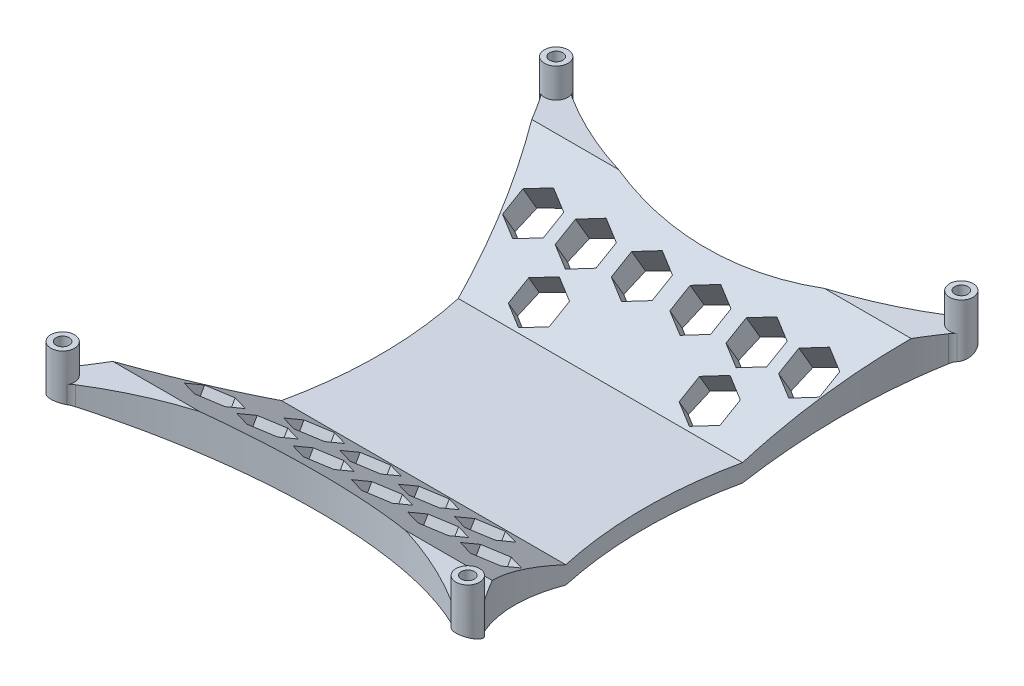
SolidWorks part; units mm, degrees
ref_plane "Front Plane" through (0, 0, 0) normal (0, 0, 1) x (1, 0, 0)
ref_plane "Top Plane" through (0, 0, 0) normal (0, 1, 0) x (1, 0, 0)
ref_plane "Right Plane" through (0, 0, 0) normal (1, 0, 0) x (0, 0, -1)
sketch "Sketch2" plane through (0, 0, 0) normal (0, 1, 0) x (1, 0, 0)
  line L0 (0, 2.54) -> (87.3125, 2.54) construction
  line L1 (89.8525, 0) -> (89.8525, -106.3625) construction
  line L2 (87.3125, -108.9025) -> (0, -108.9025) construction
  line L3 (-2.54, -106.3625) -> (-2.54, 0) construction
  line L4 (4.3994, -106.3625) -> (82.9131, -106.3625)
  line L5 (0, -101.9631) -> (0, -4.3994)
  line L6 (4.3994, 0) -> (82.9131, 0)
  line L7 (87.3125, -4.3994) -> (87.3125, -101.9631)
  circle A0 centre (0, 0) radius 1.4224
  circle A1 centre (87.3125, 0) radius 1.4224
  circle A2 centre (0, -106.3625) radius 1.4224
  circle A3 centre (87.3125, -106.3625) radius 1.4224
  arc A4 (-2.54, 0) -> (0, 2.54) centre (0, 0) cw
  arc A5 (89.8525, 0) -> (87.3125, 2.54) centre (87.3125, 0) ccw
  arc A6 (87.3125, -108.9025) -> (89.8525, -106.3625) centre (87.3125, -106.3625) ccw
  arc A7 (0, -108.9025) -> (-2.54, -106.3625) centre (0, -106.3625) cw
  arc A8 (-2.54, -106.3625) -> (-1.27, -104.1628) centre (0, -106.3625) cw
  arc A9 (0, -108.9025) -> (2.1997, -107.6325) centre (0, -106.3625) ccw
  arc A10 (-2.54, 0) -> (-1.27, -2.1997) centre (0, 0) ccw
  arc A11 (0, 2.54) -> (2.1997, 1.27) centre (0, 0) cw
  arc A12 (87.3125, 2.54) -> (85.1128, 1.27) centre (87.3125, 0) ccw
  arc A13 (88.5825, -2.1997) -> (89.8525, 0) centre (87.3125, 0) ccw
  arc A14 (85.1128, 1.27) -> (82.9131, 0) centre (82.9131, 2.54) cw
  arc A15 (87.3125, -4.3994) -> (88.5825, -2.1997) centre (89.8525, -4.3994) cw
  arc A16 (2.1997, 1.27) -> (4.3994, 0) centre (4.3994, 2.54) ccw
  arc A17 (0, -4.3994) -> (-1.27, -2.1997) centre (-2.54, -4.3994) ccw
  arc A18 (-1.27, -104.1628) -> (0, -101.9631) centre (-2.54, -101.9631) ccw
  arc A19 (2.1997, -107.6325) -> (4.3994, -106.3625) centre (4.3994, -108.9025) cw
  arc A20 (85.1128, -107.6325) -> (87.3125, -108.9025) centre (87.3125, -106.3625) ccw
  arc A21 (88.5825, -104.1628) -> (89.8525, -106.3625) centre (87.3125, -106.3625) cw
  arc A22 (82.9131, -106.3625) -> (85.1128, -107.6325) centre (82.9131, -108.9025) cw
  arc A23 (87.3125, -101.9631) -> (88.5825, -104.1628) centre (89.8525, -101.9631) ccw
  point P37 (84.7725, 0)
  point P40 (87.3125, -2.54)
  point P43 (2.54, 0)
  point P46 (0, -2.54)
  point P49 (0, -103.8225)
  point P52 (2.54, -106.3625)
  point P57 (84.7725, -106.3625)
  point P60 (87.3125, -103.8225)
  dimension "D1" = 2.8448
  dimension "D2" = 87.3125
  dimension "D8" = 2.54
  dimension "D9" = 2.54
  dimension "D10" = 2.54
  dimension "D11" = 2.54
  dimension "D20" = 2.54
  dimension "D21" = 2.54
  dimension "D22" = 2.54
  dimension "D23" = 2.54
  dimension "D24" = 2.54
  dimension "D25" = 2.54
  dimension "D26" = 2.54
  dimension "D27" = 2.54
  dimension "D3" = 106.3625
  dimension "D4" = 2.54
  dimension "D5" = 2.54
  dimension "D6" = 2.54
  dimension "D7" = 2.54
  dimension "D12" = 2.54
  dimension "D13" = 2.54
  dimension "D14" = 2.54
  dimension "D15" = 2.54
  dimension "D16" = 2.54
  dimension "D17" = 2.54
  dimension "D18" = 2.54
  dimension "D19" = 2.54
extrude "Boss-Extrude1" add sketch "Sketch2" along normal blind 19.05
sketch "Sketch3" plane through (0, 0, 0) normal (0, -1, 0) x (1, 0, 0)
  line L0 (3.1294, 106.7028) -> (84.1831, 106.7028)
  line L1 (-0.3403, 103.2331) -> (-0.3403, 3.1294)
  line L2 (3.1294, -0.3403) -> (84.1831, -0.3403)
  line L3 (87.6528, 103.2331) -> (87.6528, 3.1294)
  arc A0 (-0.3403, 103.2331) -> (-0.3403, 3.1294) centre (-73.8115, 53.1813) cw
  arc A1 (0, 101.9631) -> (-1.27, 104.1628) centre (-2.54, 101.9631) ccw construction
  arc A2 (-1.27, 2.1997) -> (0, 4.3994) centre (-2.54, 4.3994) ccw construction
  arc A3 (3.1294, 106.7028) -> (84.1831, 106.7028) centre (43.6563, 171.232) ccw
  arc A4 (2.1997, 107.6325) -> (4.3994, 106.3625) centre (4.3994, 108.9025) ccw construction
  arc A5 (82.9131, 106.3625) -> (85.1128, 107.6325) centre (82.9131, 108.9025) ccw construction
  arc A6 (87.6528, 103.2331) -> (87.6528, 3.1294) centre (161.124, 53.1813) ccw
  arc A7 (88.5825, 104.1628) -> (87.3125, 101.9631) centre (89.8525, 101.9631) ccw construction
  arc A8 (87.3125, 4.3994) -> (88.5825, 2.1997) centre (89.8525, 4.3994) ccw construction
  arc A9 (3.1294, -0.3403) -> (84.1831, -0.3403) centre (43.6562, -64.8695) cw
  arc A10 (4.3994, 0) -> (2.1997, -1.27) centre (4.3994, -2.54) ccw construction
  arc A11 (85.1128, -1.27) -> (82.9131, 0) centre (82.9131, -2.54) ccw construction
  dimension "D1" = 88.9
  dimension "D2" = 76.2
  dimension "D3" = 88.9
  dimension "D4" = 76.2
extrude "Cut-Extrude1" cut sketch "Sketch3" against normal through all
sketch "Sketch4" plane through (0, 0, 0) normal (1, 0, 0) x (0, 0, -1)
  line L0 (2.54, 15.875) -> (-34.1313, 0) construction
  line L1 (-34.1313, 0) -> (-72.2313, 0) construction
  line L2 (-72.2313, 0) -> (-108.9025, 15.875) construction
  line L4 (-108.9025, 15.875) -> (-108.9025, 0)
  line L5 (-3.1294, 0) -> (-103.2331, 0) construction
  line L6 (-3.1294, 19.05) -> (-3.1294, 0) construction
  line L7 (-103.2331, 19.05) -> (-103.2331, 0) construction
  line L8 (-108.9025, 0) -> (-72.2313, 0)
  line L9 (-72.2313, 0) -> (-108.9025, 15.875)
  line L10 (-3.1294, 0) -> (-3.1294, 19.05) construction
  line L11 (-3.1294, 19.05) -> (-103.2331, 19.05) construction
  line L12 (-103.2331, 19.05) -> (-103.2331, 0) construction
  line L15 (2.54, 0) -> (2.54, 19.05) construction
  line L16 (-3.1294, 19.05) -> (-103.2331, 19.05) construction
  line L17 (-108.9025, 19.05) -> (-108.9025, 0) construction
  line L18 (-8.0285, 19.05) -> (-34.1313, 3.81) construction
  line L19 (-34.1313, 3.81) -> (-72.2313, 3.81) construction
  line L20 (-72.2313, 3.81) -> (-98.334, 19.05) construction
  line L21 (-98.334, 19.05) -> (-103.2331, 19.05) construction
  line L22 (-8.0285, 19.05) -> (-3.1294, 19.05) construction
  line L23 (2.54, 15.875) -> (2.54, 19.05) construction
  line L24 (2.54, 19.05) -> (-3.1294, 19.05) construction
  line L25 (-103.2331, 19.05) -> (-108.9025, 19.05) construction
  line L26 (-108.9025, 19.05) -> (-108.9025, 15.875) construction
  line L27 (-98.334, 19.05) -> (-72.2313, 3.81)
  line L28 (-72.2313, 3.81) -> (-34.1313, 3.81)
  line L29 (-34.1313, 3.81) -> (-8.0285, 19.05)
  line L30 (-8.0285, 19.05) -> (-98.334, 19.05)
  line L31 (-34.1313, 0) -> (2.54, 15.875)
  line L32 (2.54, 15.875) -> (2.54, 0)
  line L33 (2.54, 0) -> (2.54, 19.05) construction
  line L34 (2.54, 0) -> (-34.1313, 0)
  point P2 (-53.1813, 0)
  point P5 (-53.1813, 19.05)
  point P16 (-53.1813, 3.81)
  point P17 (-53.1813, 0)
  dimension "D1" = 3.175
  dimension "D2" = 38.1
  dimension "D3" = 38.1
  dimension "D4" = 3.81
  dimension "D5" = 30.226
extrude "Cut-Extrude3" cut sketch "Sketch4" along normal through all and the other way through all
ref_plane "Plane1" through (0, 19.05, 0) normal (0, 1, 0) x (1, 0, 0)
sketch "Sketch5" plane through (0, 19.05, 0) normal (0, 1, 0) x (1, 0, 0)
  circle A0 centre (0, 0) radius 1.4224
  circle A1 centre (0, 0) radius 1.4224 construction
  circle A2 centre (87.3125, 0) radius 1.4224
  circle A3 centre (87.3125, 0) radius 1.4224 construction
  circle A4 centre (0, 0) radius 2.54
  circle A5 centre (87.3125, 0) radius 2.54
  circle A6 centre (87.3125, -106.3625) radius 1.4224
  circle A7 centre (87.3125, -106.3625) radius 2.54
  circle A8 centre (0, -106.3625) radius 1.4224
  circle A9 centre (0, -106.3625) radius 2.54
  arc A10 (-1.27, -104.1628) -> (2.1997, -107.6325) centre (0, -106.3625) ccw construction
  circle A11 centre (0, -106.3625) radius 1.4224 construction
  circle A12 centre (87.3125, -106.3625) radius 1.4224 construction
  arc A13 (85.1128, -107.6325) -> (88.5825, -104.1628) centre (87.3125, -106.3625) ccw construction
  arc A14 (88.5825, -2.1997) -> (85.1128, 1.27) centre (87.3125, 0) ccw construction
  arc A15 (2.1997, 1.27) -> (-1.27, -2.1997) centre (0, 0) ccw construction
extrude "Boss-Extrude2" add sketch "Sketch5" along normal blind 6.35
sketch "Sketch6" plane through (0, 0, 0) normal (0, -1, 0) x (1, 0, 0)
  line L4 (29.8133, 62.6062) -> (29.8132, 70.6803)
  line L5 (28.5856, 71.2834) -> (23.3566, 67.2464)
  line L6 (23.3566, 66.0401) -> (28.5856, 62.0031)
  line L7 (57.4993, 62.6062) -> (57.4993, 70.6803)
  line L8 (58.7269, 71.2834) -> (63.9559, 67.2464)
  line L9 (63.9559, 66.0401) -> (58.7269, 62.0031)
  line L10 (74.2891, 72.2313) -> (13.0234, 72.2313) construction
  line L11 (74.2891, 34.1313) -> (13.0234, 34.1313) construction
  line L12 (73.2492, 66.6432) -> (14.0633, 66.6432) construction
  line L13 (43.6562, 72.2313) -> (43.6562, 34.1313) construction
  line L14 (29.8133, 66.6432) -> (57.4992, 66.6432) construction
  arc A0 (74.2891, 72.2313) -> (74.2891, 34.1313) centre (161.124, 53.1813) ccw construction
  arc A1 (13.0234, 34.1313) -> (13.0234, 72.2313) centre (-73.8115, 53.1813) ccw construction
  arc A2 (63.9559, 66.0401) -> (63.9559, 67.2464) centre (63.4902, 66.6432) ccw
  arc A3 (58.7269, 71.2834) -> (57.4993, 70.6803) centre (58.2613, 70.6803) ccw
  arc A4 (57.4993, 62.6062) -> (58.7269, 62.0031) centre (58.2613, 62.6062) ccw
  arc A5 (23.3566, 66.0401) -> (23.3566, 67.2464) centre (23.8223, 66.6432) cw
  arc A6 (28.5856, 62.0031) -> (29.8133, 62.6062) centre (29.0512, 62.6062) ccw
  arc A7 (28.5856, 71.2834) -> (29.8132, 70.6803) centre (29.0512, 70.6803) cw
  point P0 (0, 0)
  point P2 (43.6562, 34.1313)
  point P20 (43.6562, 66.6432)
  point P22 (43.6562, 72.2313)
  point P28 (0, 0)
  point P29 (49.6148, 8.6596)
  point P30 (65.1158, 55.08)
  point P31 (47.1781, 12.0955)
  point P32 (64.7371, 66.6432)
  point P33 (22.5754, 56.3199)
  point P34 (64.7371, 56.8697)
  point P35 (40.9992, 14.6764)
  point P36 (47.9433, 14.6597)
  point P37 (0, 0)
  point P38 (0, 0)
  point P39 (50.2602, 12.8252)
  point P40 (43.6562, 9.9882)
  point P41 (43.7811, 33.0427)
  point P42 (44.1642, 18.4996)
  point P43 (43.6562, 15.5951)
  point P44 (0, 0)
  point P45 (43.6562, 15.5627)
  point P46 (43.6562, 57.7512)
  point P49 (57.4993, 72.2313)
  point P52 (57.4993, 61.0553)
  point P55 (22.5754, 66.6432)
  point P58 (29.8133, 61.0553)
  point P61 (29.8132, 72.2313)
  dimension "D2" = 0.762
  dimension "D1" = 27.686
  dimension "D4" = 9.144
  dimension "D5" = 11.176
extrude "Boss-Extrude3" add sketch "Sketch6" along normal blind 7.9375
sketch "Sketch7" plane through (0, 0, 0) normal (0, -1, 0) x (1, 0, 0)
  line L0 (43.6562, 72.2313) -> (43.6563, 11.3305) construction
  line L1 (74.2891, 72.2313) -> (13.0234, 72.2313) construction
  line L2 (43.0142, 27.4701) -> (40.8494, 24.0824)
  line L3 (41.4915, 22.9101) -> (45.821, 22.9101)
  line L4 (46.4631, 24.0824) -> (44.2983, 27.4701)
  arc A0 (84.1831, -0.3403) -> (3.1294, -0.3403) centre (43.6562, -64.8695) ccw construction
  arc A2 (57.4993, 62.6062) -> (58.7269, 62.0031) centre (58.2613, 62.6062) ccw construction
  arc A3 (40.8494, 24.0824) -> (41.4915, 22.9101) centre (41.4915, 23.6721) ccw
  arc A4 (45.821, 22.9101) -> (46.4631, 24.0824) centre (45.821, 23.6721) ccw
  arc A5 (43.0142, 27.4701) -> (44.2983, 27.4701) centre (43.6562, 27.0598) cw
  point P9 (43.6562, 22.9101)
  point P11 (49.0366, 23.1811)
  point P17 (40.1002, 22.9101)
  point P20 (47.2123, 22.9101)
  point P23 (43.6562, 28.475)
  dimension "D3" = 34.1313
  dimension "D4" = 0.762
  dimension "D1" = 6.604
  dimension "D2" = 7.112
extrude "Boss-Extrude4" add sketch "Sketch7" along normal up to surface and the other way up to next
ref_plane "Plane2" through (0, 0, 0) normal (0, -1, 0) x (-1, 0, 0)
sketch "Sketch8" plane through (0, 0, 0) normal (0, -1, 0) x (1, 0, 0)
  line L0 (43.6562, 27.8218) -> (43.6562, 22.9101) construction
  line L1 (45.821, 22.9101) -> (41.4915, 22.9101) construction
  line L2 (41.9318, 25.7763) -> (45.3807, 25.7763) construction
  line L3 (40.8494, 24.0824) -> (43.0142, 27.4701) construction
  line L4 (44.2983, 27.4701) -> (46.4631, 24.0824) construction
  circle A0 centre (43.6562, 25.7763) radius 6.35
  arc A1 (44.2983, 27.4701) -> (43.0142, 27.4701) centre (43.6562, 27.0598) ccw construction
  point P15 (0, 0)
  point P17 (43.6562, 25.7763)
  dimension "D1" = 12.7
extrude "Boss-Extrude5" add sketch "Sketch8" against normal up to next
sketch "Sketch9" plane through (0, -28.6096, 16.7036) normal (0, 0.8636, -0.5042) x (1, 0, 0)
  line L1 (73.287, -76.7449) -> (68.8876, -79.2849)
  line L2 (68.8876, -79.2849) -> (68.8876, -84.3649)
  line L3 (68.8876, -84.3649) -> (73.287, -86.9049)
  line L4 (73.287, -86.9049) -> (77.6864, -84.3649)
  line L5 (77.6864, -84.3649) -> (77.6864, -79.2849)
  line L6 (77.6864, -79.2849) -> (73.287, -76.7449)
  line L66 (79.0595, -81.8249) -> (8.253, -81.8249) construction
  line L67 (77.1356, -75.9829) -> (10.1769, -75.9829) construction
  line L68 (61.9482, -76.7449) -> (57.5488, -79.2849)
  line L69 (57.5488, -79.2849) -> (57.5488, -84.3649)
  line L70 (57.5488, -84.3649) -> (61.9482, -86.9049)
  line L71 (61.9482, -86.9049) -> (66.3476, -84.3649)
  line L72 (66.3476, -84.3649) -> (66.3476, -79.2849)
  line L73 (66.3476, -79.2849) -> (61.9482, -76.7449)
  line L74 (49.8474, -76.7449) -> (45.448, -79.2849)
  line L75 (45.448, -79.2849) -> (45.448, -84.3649)
  line L76 (45.448, -84.3649) -> (49.8474, -86.9049)
  line L77 (49.8474, -86.9049) -> (54.2468, -84.3649)
  line L78 (54.2468, -84.3649) -> (54.2468, -79.2849)
  line L79 (54.2468, -79.2849) -> (49.8474, -76.7449)
  line L80 (37.2385, -76.7449) -> (32.8391, -79.2849)
  line L81 (32.8391, -79.2849) -> (32.8391, -84.3649)
  line L82 (32.8391, -84.3649) -> (37.2385, -86.9049)
  line L83 (37.2385, -86.9049) -> (41.638, -84.3649)
  line L84 (41.638, -84.3649) -> (41.638, -79.2849)
  line L85 (41.638, -79.2849) -> (37.2385, -76.7449)
  line L86 (25.1377, -76.7449) -> (20.7383, -79.2849)
  line L87 (20.7383, -79.2849) -> (20.7383, -84.3649)
  line L88 (20.7383, -84.3649) -> (25.1377, -86.9049)
  line L89 (25.1377, -86.9049) -> (29.5371, -84.3649)
  line L90 (29.5371, -84.3649) -> (29.5371, -79.2849)
  line L91 (29.5371, -79.2849) -> (25.1377, -76.7449)
  line L92 (13.7989, -76.7449) -> (9.3995, -79.2849)
  line L93 (9.3995, -79.2849) -> (9.3995, -84.3649)
  line L94 (9.3995, -84.3649) -> (13.7989, -86.9049)
  line L95 (13.7989, -86.9049) -> (18.1983, -84.3649)
  line L96 (18.1983, -84.3649) -> (18.1983, -79.2849)
  line L97 (18.1983, -79.2849) -> (13.7989, -76.7449)
  line L122 (29.5371, -72.6809) -> (25.1377, -75.2209)
  line L123 (29.5371, -67.6009) -> (29.5371, -72.6809)
  line L124 (25.1377, -65.0609) -> (29.5371, -67.6009)
  line L125 (20.7383, -67.6009) -> (25.1377, -65.0609)
  line L126 (20.7383, -72.6809) -> (20.7383, -67.6009)
  line L127 (25.1377, -75.2209) -> (20.7383, -72.6809)
  line L128 (41.638, -72.6809) -> (37.2385, -75.2209)
  line L129 (41.638, -67.6009) -> (41.638, -72.6809)
  line L130 (37.2385, -65.0609) -> (41.638, -67.6009)
  line L131 (32.8391, -67.6009) -> (37.2385, -65.0609)
  line L132 (32.8391, -72.6809) -> (32.8391, -67.6009)
  line L133 (37.2385, -75.2209) -> (32.8391, -72.6809)
  line L134 (54.2468, -72.6809) -> (49.8474, -75.2209)
  line L135 (54.2468, -67.6009) -> (54.2468, -72.6809)
  line L136 (49.8474, -65.0609) -> (54.2468, -67.6009)
  line L137 (45.448, -67.6009) -> (49.8474, -65.0609)
  line L138 (45.448, -72.6809) -> (45.448, -67.6009)
  line L139 (49.8474, -75.2209) -> (45.448, -72.6809)
  line L140 (66.3476, -72.6809) -> (61.9482, -75.2209)
  line L141 (66.3476, -67.6009) -> (66.3476, -72.6809)
  line L142 (61.9482, -65.0609) -> (66.3476, -67.6009)
  line L143 (57.5488, -67.6009) -> (61.9482, -65.0609)
  line L144 (57.5488, -72.6809) -> (57.5488, -67.6009)
  line L145 (61.9482, -75.2209) -> (57.5488, -72.6809)
  circle A0 centre (73.287, -81.8249) radius 4.3994 construction
  circle A1 centre (61.9482, -81.8249) radius 4.3994 construction
  circle A2 centre (49.8474, -81.8249) radius 4.3994 construction
  circle A3 centre (37.2385, -81.8249) radius 4.3994 construction
  circle A4 centre (25.1377, -81.8249) radius 4.3994 construction
  circle A5 centre (13.7989, -81.8249) radius 4.3994 construction
  ellipse E0 centre (161.124, -42.2397) end of major axis (161.124, -145.1826) minor radius 88.9 (74.2891, -64.2989) -> (84.5444, -94.5249) ccw construction
  ellipse E1 centre (-73.8115, -42.2397) end of major axis (-73.8115, 60.7031) minor radius 88.9 (2.7681, -94.5249) -> (13.0234, -64.2989) ccw construction
  dimension "D1" = 5.08
  dimension "D2" = 6.858
  dimension "D3" = 12.7
  dimension "D4" = 2.54
  dimension "D5" = 3.302
  dimension "D6" = 3.81
  dimension "D7" = 3.302
  dimension "D8" = 2.54
  dimension "D9" = 0.762
extrude "Cut-Extrude4" cut sketch "Sketch9" against normal through all
sketch "Sketch11" plane through (0, 35.7059, -20.4993) normal (0, -0.8636, -0.5042) x (1, 0, 0)
  line L1 (73.5136, 50.8141) -> (69.1142, 48.2741)
  line L2 (69.1142, 48.2741) -> (69.1142, 43.1941)
  line L3 (69.1142, 43.1941) -> (73.5136, 40.6541)
  line L4 (73.5136, 40.6541) -> (77.913, 43.1941)
  line L5 (77.913, 43.1941) -> (77.913, 48.2741)
  line L6 (77.913, 48.2741) -> (73.5136, 50.8141)
  line L66 (79.0595, 45.7341) -> (8.253, 45.7341) construction
  line L67 (77.1356, 51.5761) -> (10.1769, 51.5761) construction
  line L68 (62.1748, 50.8141) -> (57.7754, 48.2741)
  line L69 (57.7754, 48.2741) -> (57.7754, 43.1941)
  line L70 (57.7754, 43.1941) -> (62.1748, 40.6541)
  line L71 (62.1748, 40.6541) -> (66.5742, 43.1941)
  line L72 (66.5742, 43.1941) -> (66.5742, 48.2741)
  line L73 (66.5742, 48.2741) -> (62.1748, 50.8141)
  line L74 (50.074, 50.8141) -> (45.6745, 48.2741)
  line L75 (45.6745, 48.2741) -> (45.6745, 43.1941)
  line L76 (45.6745, 43.1941) -> (50.074, 40.6541)
  line L77 (50.074, 40.6541) -> (54.4734, 43.1941)
  line L78 (54.4734, 43.1941) -> (54.4734, 48.2741)
  line L79 (54.4734, 48.2741) -> (50.074, 50.8141)
  line L80 (37.4651, 50.8141) -> (33.0657, 48.2741)
  line L81 (33.0657, 48.2741) -> (33.0657, 43.1941)
  line L82 (33.0657, 43.1941) -> (37.4651, 40.6541)
  line L83 (37.4651, 40.6541) -> (41.8645, 43.1941)
  line L84 (41.8645, 43.1941) -> (41.8645, 48.2741)
  line L85 (41.8645, 48.2741) -> (37.4651, 50.8141)
  line L86 (25.3643, 50.8141) -> (20.9649, 48.2741)
  line L87 (20.9649, 48.2741) -> (20.9649, 43.1941)
  line L88 (20.9649, 43.1941) -> (25.3643, 40.6541)
  line L89 (25.3643, 40.6541) -> (29.7637, 43.1941)
  line L90 (29.7637, 43.1941) -> (29.7637, 48.2741)
  line L91 (29.7637, 48.2741) -> (25.3643, 50.8141)
  line L92 (14.0255, 50.8141) -> (9.6261, 48.2741)
  line L93 (9.6261, 48.2741) -> (9.6261, 43.1941)
  line L94 (9.6261, 43.1941) -> (14.0255, 40.6541)
  line L95 (14.0255, 40.6541) -> (18.4249, 43.1941)
  line L96 (18.4249, 43.1941) -> (18.4249, 48.2741)
  line L97 (18.4249, 48.2741) -> (14.0255, 50.8141)
  line L122 (29.7637, 54.8781) -> (25.3643, 52.3381)
  line L123 (29.7637, 59.9581) -> (29.7637, 54.8781)
  line L124 (25.3643, 62.4981) -> (29.7637, 59.9581)
  line L125 (20.9649, 59.9581) -> (25.3643, 62.4981)
  line L126 (20.9649, 54.8781) -> (20.9649, 59.9581)
  line L127 (25.3643, 52.3381) -> (20.9649, 54.8781)
  line L140 (66.5742, 54.8781) -> (62.1748, 52.3381)
  line L141 (66.5742, 59.9581) -> (66.5742, 54.8781)
  line L142 (62.1748, 62.4981) -> (66.5742, 59.9581)
  line L143 (57.7754, 59.9581) -> (62.1748, 62.4981)
  line L144 (57.7754, 54.8781) -> (57.7754, 59.9581)
  line L145 (62.1748, 52.3381) -> (57.7754, 54.8781)
  circle A0 centre (73.5136, 45.7341) radius 4.3994 construction
  circle A1 centre (62.1748, 45.7341) radius 4.3994 construction
  circle A2 centre (50.074, 45.7341) radius 4.3994 construction
  circle A3 centre (37.4651, 45.7341) radius 4.3994 construction
  circle A4 centre (25.3643, 45.7341) radius 4.3994 construction
  circle A5 centre (14.0255, 45.7341) radius 4.3994 construction
  ellipse E2 centre (161.124, 85.3193) end of major axis (161.124, 188.2622) minor radius 88.9 (74.2891, 63.2601) -> (84.5444, 33.0341) ccw construction
  ellipse E3 centre (-73.8115, 85.3193) end of major axis (-73.8115, 188.2622) minor radius 88.9 (2.7681, 33.0341) -> (13.0234, 63.2601) ccw construction
  point P41 (0, 0)
  point P56 (0, 0)
  point P74 (0, 0)
  point P75 (0, 0)
  point P76 (14.0255, 37.2741)
  dimension "D1" = 5.08
  dimension "D2" = 6.858
  dimension "D3" = 15.24
  dimension "D4" = 2.54
  dimension "D5" = 3.302
  dimension "D6" = 3.81
  dimension "D7" = 3.302
  dimension "D8" = 2.54
  dimension "D9" = 0.762
extrude "Cut-Extrude5" cut sketch "Sketch11" along normal blind 7.9375
